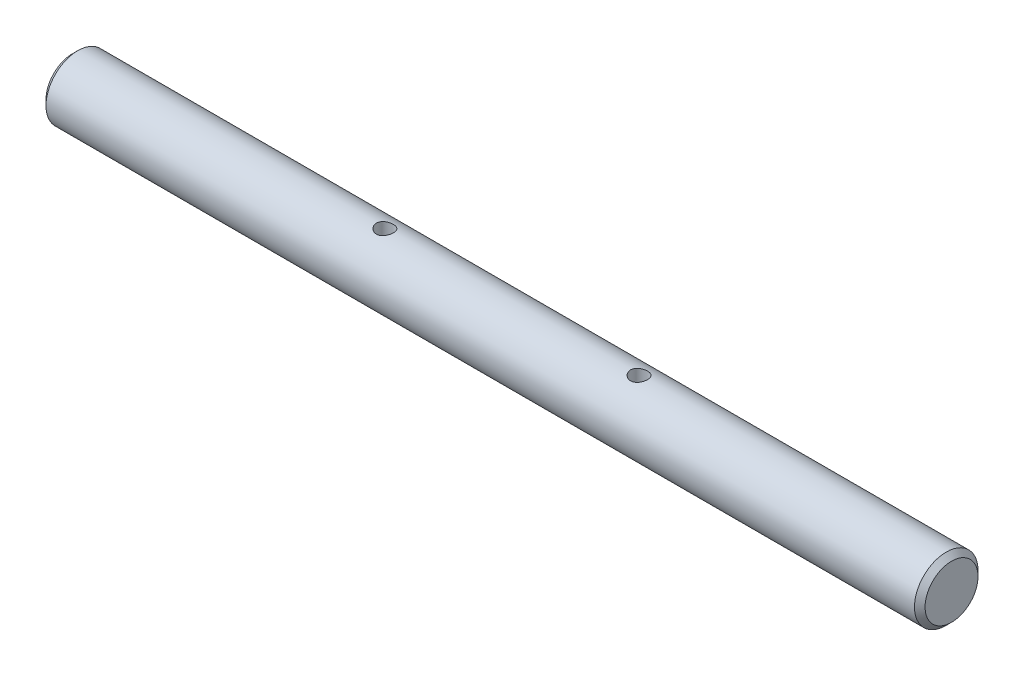
SolidWorks part; units mm, degrees
material "45"
ref_plane "前视基准面" through (0, 0, 0) normal (0, 0, 1) x (1, 0, 0)
ref_plane "上视基准面" through (0, 0, 0) normal (0, 1, 0) x (1, 0, 0)
ref_plane "右视基准面" through (0, 0, 0) normal (1, 0, 0) x (0, 0, -1)
sketch "草图1" plane through (0, 0, 0) normal (0, 0, 1) x (1, 0, 0)
  line L0 (0, 0) -> (-864.1669, 0) construction
  line L1 (-830, 0) -> (-830, 30)
  line L2 (-830, 30) -> (0, 30)
  line L3 (0, 30) -> (0, 0)
  line L4 (-830, 0) -> (0, 0)
  dimension "D1" = 830
  dimension "D2" = 60
revolve "旋转1" add sketch "草图1" angle 360 about L0
chamfer "倒角1" distance 5 angle 45 2 edges at (-830, 30, 0) (0, 30, 0)
ref_plane "基准面1" through (0, 30, 0) normal (0, 1, 0) x (1, 0, 0)
sketch "草图2" plane through (0, 30, 0) normal (0, 1, 0) x (1, 0, 0)
  line L0 (0, 0) -> (-830, 0) construction
  line L1 (-830, 25) -> (-830, -25) construction
  point P3 (-535, 0)
  point P4 (-295, 0)
  dimension "D1" = 295
  dimension "D2" = 240
hole_wizard "Ø16.0 (16) 直径孔1" positions "草图3" profile "草图4" hole size "Ø16.0" standard "GB"
sketch "草图3" plane through (0, 30, 0) normal (0, 1, 0) x (1, 0, 0)
  point P0 (-535, 0)
  point P3 (-295, 0)
sketch "草图4" plane through (-535, 30, 0) normal (1, 0, 0) x (0, 0, 1)
  line L0 (0, 0) -> (0, 19.8069)
  line L1 (0, 19.8069) -> (8, 15)
  line L2 (8, 15) -> (8, 0)
  line L5 (8, 0) -> (0, 0)
  line L10 (0, 19.8069) -> (-8, 15) construction
  line L11 (0, -6.35) -> (0, 107.95) construction
  dimension "孔直径" = 16
  dimension "孔深度" = 15
  dimension "导头角度" = 118
